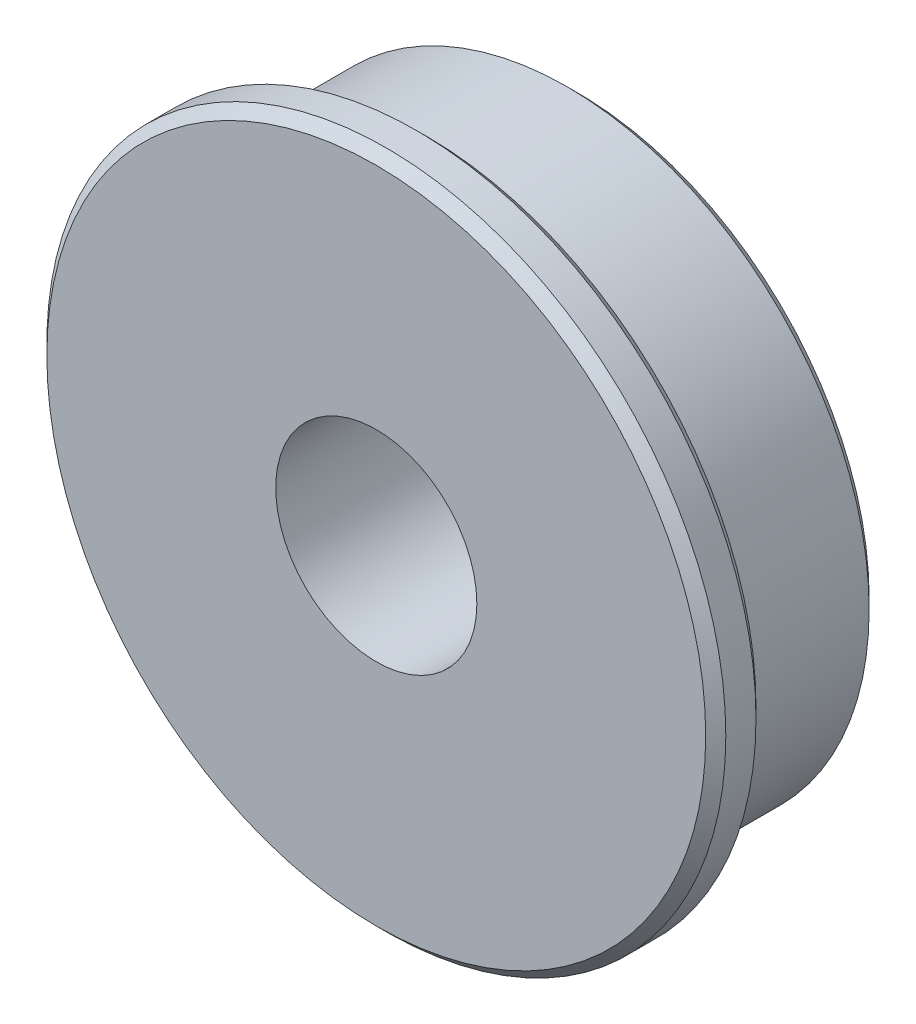
SolidWorks part; units mm, degrees
ref_plane "前视基准面" through (0, 0, 0) normal (0, 0, 1) x (1, 0, 0)
ref_plane "上视基准面" through (0, 0, 0) normal (0, 1, 0) x (1, 0, 0)
ref_plane "右视基准面" through (0, 0, 0) normal (1, 0, 0) x (0, 0, -1)
sketch "草图1" plane through (0, 0, 0) normal (0, 0, 1) x (1, 0, 0)
  circle A0 centre (0, 0) radius 6
  circle A1 centre (0, 0) radius 2
  dimension "D1" = 12
  dimension "D2" = 4
extrude "凸台-拉伸1" add sketch "草图1" along normal mid plane 4
sketch "草图2" plane through (0, 0, 2) normal (0, 0, 1) x (1, 0, 0)
  circle A0 centre (0, 0) radius 6.75
  circle A2 centre (0, 0) radius 2 construction
  circle A3 centre (0, 0) radius 2
  dimension "D1" = 13.5
extrude "凸台-拉伸2" add sketch "草图2" against normal blind 1
chamfer "倒角1" distance 0.2 angle 45 3 edges at (6, 0, -2) (6.75, 0, 1) (6.75, 0, 2)
